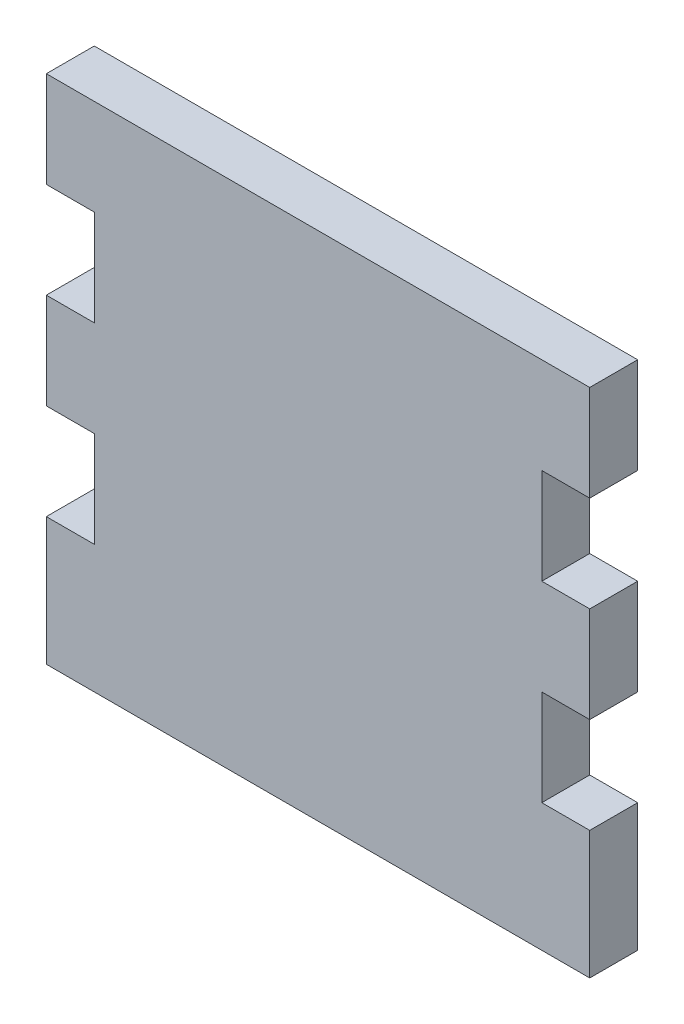
SolidWorks part; units mm, degrees
ref_plane "Front Plane" through (0, 0, 0) normal (0, 0, 1) x (1, 0, 0)
ref_plane "Top Plane" through (0, 0, 0) normal (0, 1, 0) x (1, 0, 0)
ref_plane "Right Plane" through (0, 0, 0) normal (1, 0, 0) x (0, 0, -1)
sketch "Sketch1" plane through (0, 0, 0) normal (0, 0, 1) x (1, 0, 0)
  line L1 (-397.2632, 209.59) -> (-227.2632, 209.59)
  line L2 (-382.2632, 339.59) -> (-397.2632, 339.59)
  line L3 (-397.2632, 369.59) -> (-227.2632, 369.59)
  line L4 (-227.2632, 209.59) -> (-227.2632, 249.59)
  line L5 (-227.2632, 249.59) -> (-242.2632, 249.59)
  line L6 (-312.2632, 369.59) -> (-312.2632, 209.59) construction
  line L7 (-242.2632, 249.59) -> (-242.2632, 279.59)
  line L8 (-242.2632, 279.59) -> (-242.2632, 249.59) construction
  line L9 (-242.2632, 279.59) -> (-227.2632, 279.59)
  line L10 (-227.2632, 279.59) -> (-227.2632, 309.59)
  line L11 (-227.2632, 309.59) -> (-242.2632, 309.59)
  line L12 (-242.2632, 309.59) -> (-242.2632, 339.59)
  line L13 (-242.2632, 339.59) -> (-242.2632, 309.59) construction
  line L14 (-382.2632, 309.59) -> (-382.2632, 339.59)
  line L15 (-397.2632, 309.59) -> (-382.2632, 309.59)
  line L16 (-397.2632, 279.59) -> (-397.2632, 309.59)
  line L17 (-382.2632, 279.59) -> (-397.2632, 279.59)
  line L18 (-382.2632, 249.59) -> (-382.2632, 279.59)
  line L19 (-397.2632, 249.59) -> (-382.2632, 249.59)
  line L20 (-397.2632, 339.59) -> (-397.2632, 369.59)
  line L21 (-397.2632, 249.59) -> (-397.2632, 209.59)
  line L22 (-242.2632, 339.59) -> (-227.2632, 339.59)
  line L23 (-227.2632, 339.59) -> (-227.2632, 369.59)
  point P36 (-397.8485, 209.59)
  dimension "D1" = 160
  dimension "D2" = 170
extrude "Boss-Extrude1" add sketch "Sketch1" along normal blind 15
